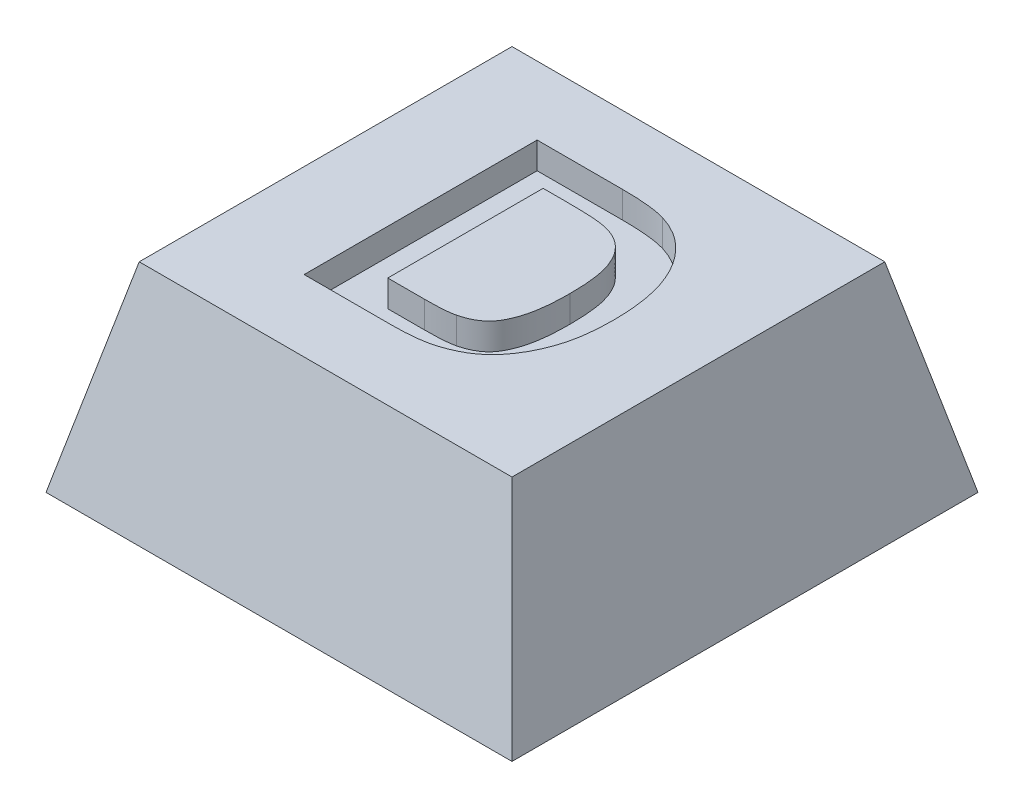
SolidWorks part; units mm, degrees
ref_plane "Front Plane" through (0, 0, 0) normal (0, 0, 1) x (1, 0, 0)
ref_plane "Top Plane" through (0, 0, 0) normal (0, 1, 0) x (1, 0, 0)
ref_plane "Right Plane" through (0, 0, 0) normal (1, 0, 0) x (0, 0, -1)
sketch "Sketch1" plane through (0, 0, 0) normal (0, 1, 0) x (1, 0, 0)
  line L1 (0, 0) -> (7, 0)
  line L2 (0, 0) -> (0, 7)
  line L3 (0, 7) -> (7, 7)
  line L4 (7, 0) -> (7, 7)
  dimension "D1" = 7
  dimension "D2" = 7
extrude "Boss-Extrude1" add sketch "Sketch1" along normal blind 3
sketch "Sketch2" plane through (0, 0, 0) normal (0, 0, 1) x (1, 0, 0)
  line L0 (0, 0) -> (0.7, 3)
  line L1 (0, 3) -> (7, 3) construction
  line L2 (0.7, 3) -> (0, 3)
  line L3 (0, 3) -> (0, 0)
  line L4 (7, 0) -> (6.3, 3)
  line L5 (6.3, 3) -> (7, 3)
  line L6 (7, 3) -> (7, 0)
  dimension "D1" = 0.7
  dimension "D2" = 0.7
extrude "Cut-Extrude1" cut sketch "Sketch2" against normal blind 7
sketch "Sketch3" plane through (0, 0, 0) normal (1, 0, 0) x (0, 0, -1)
  line L0 (0, 0) -> (0.7, 3)
  line L1 (7, 3) -> (0, 3) construction
  line L2 (0.7, 3) -> (0, 3)
  line L3 (0, 3) -> (0, 0)
  line L4 (7, 3) -> (6.3, 3)
  line L5 (6.3, 3) -> (7, 0)
  line L6 (7, 3) -> (7, 0)
  dimension "D1" = 0.7
  dimension "D2" = 0.7
extrude "Cut-Extrude2" cut sketch "Sketch3" along normal blind 11
sketch "Sketch4" plane through (0, 0, 0) normal (0, -1, 0) x (1, 0, 0)
  line L0 (3.5, 0) -> (3.5, -7) construction
  line L1 (0, 0) -> (7, 0) construction
  line L2 (7, -7) -> (0, -7) construction
  line L3 (0, -3.5) -> (7, -3.5) construction
  line L4 (0, -7) -> (0, 0) construction
  line L5 (7, 0) -> (7, -7) construction
  circle A0 centre (3.5, -3.5) radius 1.8
  dimension "D1" = 3.6
extrude "Cut-Extrude3" cut sketch "Sketch4" against normal blind 0.8
sketch "Sketch5" plane through (0, 3, 0) normal (0, 1, 0) x (1, 0, 0)
  text T0 "D" font "Arial" height 3.5
extrude "Cut-Extrude4" cut sketch "Sketch5" against normal blind 0.4
